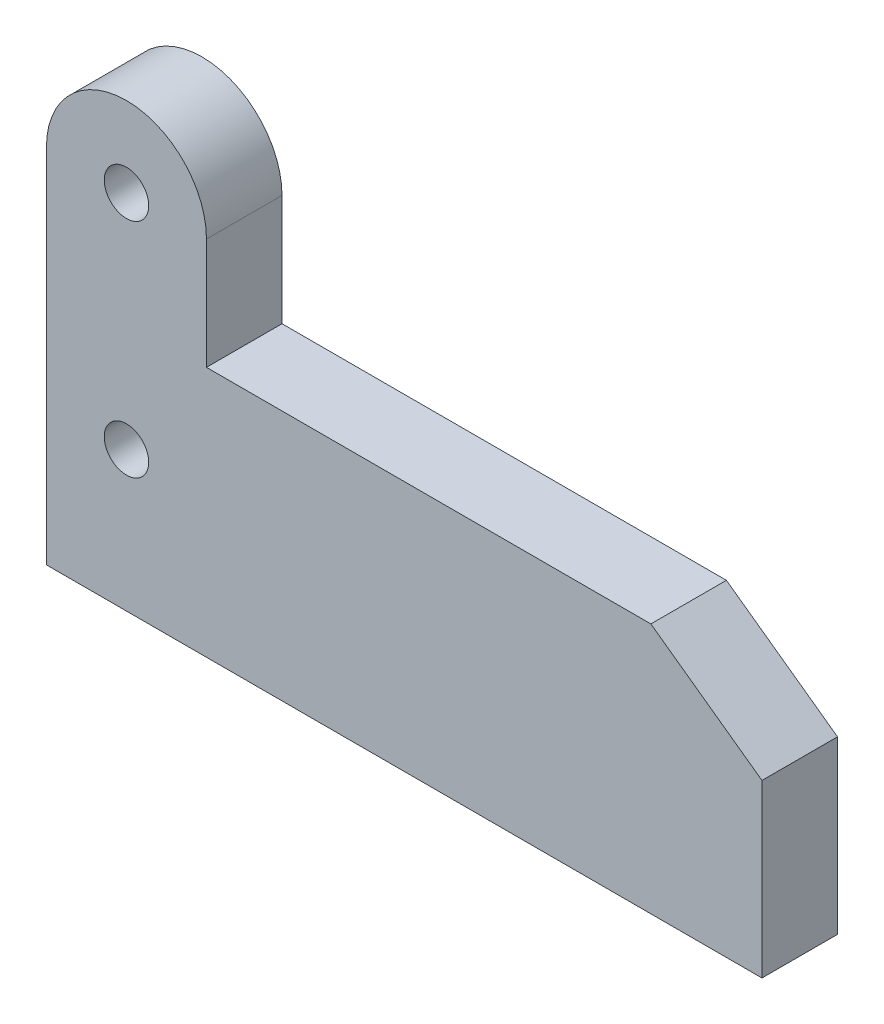
SolidWorks part; units mm, degrees
ref_plane "Front" through (0, 0, 0) normal (0, 0, 1) x (1, 0, 0)
ref_plane "Top" through (0, 0, 0) normal (0, 1, 0) x (1, 0, 0)
ref_plane "Right" through (0, 0, 0) normal (1, 0, 0) x (0, 0, -1)
sketch "Croquis1" plane through (0, 0, 0) normal (0, 0, 1) x (1, 0, 0)
  line L0 (0, 0) -> (0, -10) construction
  line L1 (-3.6, 0) -> (-3.6, -10)
  line L2 (3.6, 0) -> (3.6, -5)
  line L3 (3.6, -5) -> (23.6, -5)
  line L4 (0, -13.6) -> (28.6, -13.6)
  line L5 (28.6, -13.6) -> (28.6, -8.6)
  line L6 (28.6, -8.6) -> (23.6, -5)
  circle A0 centre (0, 0) radius 1
  circle A1 centre (0, -10) radius 1
  arc A2 (3.6, 0) -> (-3.6, 0) centre (0, 0) ccw
  arc A3 (-3.6, -10) -> (0, -13.6) centre (0, -10) ccw
  dimension "D1" = 2
  dimension "D3" = 7.2
  dimension "D2" = 10
  dimension "D4" = 20
  dimension "D5" = 5
  dimension "D6" = 5
extrude "Saliente-Extruir1" add sketch "Croquis1" along normal mid plane 3.4
sketch "Croquis2" plane through (28.6, 0, 0) normal (1, 0, 0) x (0, 0, -1)
  line L4 (1.7, -13.6) -> (-0.3, -9.6)
  line L5 (-0.3, -9.6) -> (1.7, -9.6)
  line L6 (1.7, -13.6) -> (1.7, -8.6) construction
  line L7 (1.7, -9.6) -> (1.7, -13.6)
  dimension "D1" = 4
  dimension "D2" = 2
sketch "Croquis3" plane through (0, 0, -1.7) normal (0, 0, -1) x (-1, 0, 0)
  line L4 (-28.6, -13.6) -> (-28.6, -24.59)
  line L5 (-28.6, -24.59) -> (-13.6, -24.59)
  line L6 (-13.6, -24.59) -> (-13.6, -13.6)
  line L8 (0, -13.6) -> (-28.6, -13.6) construction
  line L9 (-13.6, -13.6) -> (-28.6, -13.6)
  circle A1 centre (0, 0) radius 1 construction
  dimension "D1" = 24.59
  dimension "D2" = 15
extrude "Saliente-Extruir2" add sketch "Croquis3" against normal up to surface (3.4 mm away) up to face at (1, 0, 1.7)
sketch "Croquis4" plane through (0, -24.59, 0) normal (0, -1, 0) x (1, 0, 0)
  line L4 (28.6, -1.7) -> (28.6, 1.7)
  line L5 (28.6, 1.7) -> (13.6, 1.7)
  line L6 (13.6, 1.7) -> (13.6, -1.7)
  line L7 (13.6, -1.7) -> (28.6, -1.7)
  line L8 (28.6, -1.7) -> (28.6, 1.7)
  line L9 (28.6, 1.7) -> (13.6, 1.7)
  line L10 (13.6, 1.7) -> (13.6, -1.7)
  line L11 (13.6, -1.7) -> (28.6, -1.7)
  dimension "D1" = 0
extrude "Cortar-Extruir1" cut sketch "Croquis4" against normal up to surface (10.99 mm away) up to face at (6.8, -13.6, 0)
sketch "Croquis5" plane through (0, 0, 1.7) normal (0, 0, 1) x (1, 0, 0)
  line L0 (28.6, -13.6) -> (28.6, -16.3)
  line L1 (28.6, -16.3) -> (-3.6, -16.3)
  line L2 (-3.6, -16.3) -> (-3.6, -10)
  line L3 (-3.6, 0) -> (-3.6, -10) construction
  line L4 (0, -13.6) -> (28.6, -13.6) construction
  line L5 (0, -13.6) -> (28.6, -13.6)
  arc A0 (-3.6, -10) -> (0, -13.6) centre (0, -10) ccw construction
  arc A1 (-3.6, -10) -> (0, -13.6) centre (0, -10) ccw
  dimension "D1" = 2.7
extrude "Saliente-Extruir3" add sketch "Croquis5" against normal up to surface (3.4 mm away) up to face at (10.0068, -6.6182, -1.7)
